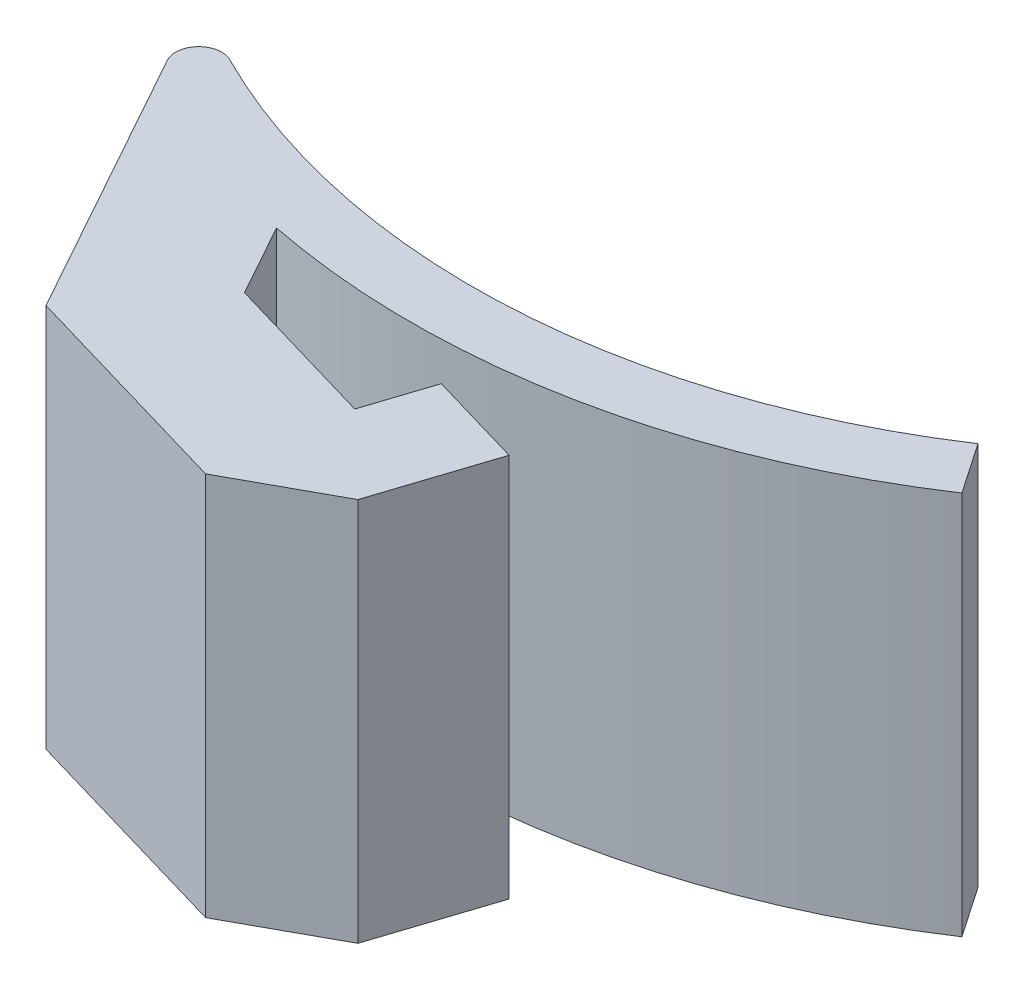
SolidWorks part; units mm, degrees
ref_plane "Спереди" through (0, 0, 0) normal (0, 0, 1) x (1, 0, 0)
ref_plane "Сверху" through (0, 0, 0) normal (0, 1, 0) x (1, 0, 0)
ref_plane "Справа" through (0, 0, 0) normal (1, 0, 0) x (0, 0, -1)
sketch "Эскиз1" plane through (0, 0, 0) normal (0, 1, 0) x (1, 0, 0)
  line L0 (4.2452, -5.0108) -> (4.7271, -3.3642) construction
  line L1 (2.5, -4.5) -> (6.3951, -5.64)
  line L2 (6.3951, -5.64) -> (7.2, -3.175)
  line L3 (7.2, -3.175) -> (5.9523, -2.8099)
  line L4 (5.9523, -2.8099) -> (5.6754, -3.658)
  line L5 (5.6754, -3.658) -> (3.6472, -3.0644)
  line L6 (3.6472, -3.0644) -> (3.1268, -2.1278)
  line L7 (10.12, 0.0055) -> (10.5711, -0.6553)
  line L9 (0.5267, -0.9481) -> (2.5, -4.5)
  line L10 (2.1224, -3.8203) -> (3.5998, -2.9995) construction
  arc A0 (0.9239, -0.5345) -> (10.12, 0.0055) centre (5.0558, 7.6737) ccw
  arc A1 (3.1268, -2.1278) -> (10.5711, -0.6553) centre (5.0558, 7.6737) ccw
  arc A3 (-0.4009, -0.6938) -> (10.5609, -0.6621) centre (5.0558, 7.6737) ccw construction
  arc A4 (0.0361, -0.0237) -> (10.12, 0.0055) centre (5.0558, 7.6737) ccw construction
  arc A5 (0.9239, -0.5345) -> (0.5267, -0.9481) centre (0.789, -0.8024) ccw
  point P12 (3.1251, -2.9116)
  point P14 (3.6084, -2.9947)
  point P18 (5.5945, -1.5)
  point P25 (4.7228, -3.3792)
  point P26 (0, 0)
  point P27 (0.7605, -0.5038)
  dimension "D8" = 0.3
  dimension "D1" = 10.12
  dimension "D2" = 1.7
  dimension "D3" = 4.5
  dimension "D4" = 2.5
  dimension "D5" = 7.2
  dimension "D6" = 5.64
  dimension "D7" = 1.3
  dimension "D9" = 1.7
  dimension "D11" = 1.5
  dimension "D12" = 0.8
extrude "Бобышка-Вытянуть1" add sketch "Эскиз1" along normal blind 5
chamfer "Фаска1" distance 1 angle 45 1 edges at (6.3951, 2.5, 5.64)
